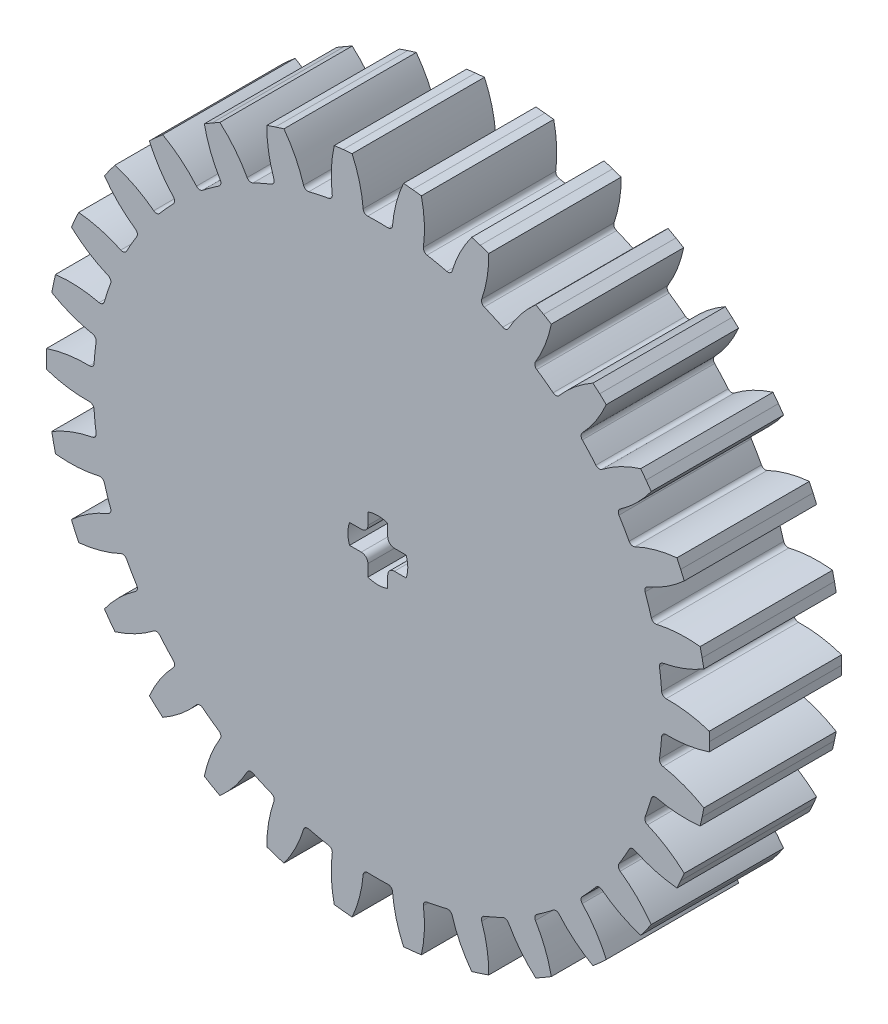
SolidWorks part; units mm, degrees
ref_plane "Front Plane" through (0, 0, 0) normal (0, 0, 1) x (1, 0, 0)
ref_plane "Top Plane" through (0, 0, 0) normal (0, 1, 0) x (1, 0, 0)
ref_plane "Right Plane" through (0, 0, 0) normal (1, 0, 0) x (0, 0, -1)
sketch "Sketch1" plane through (0, 0, 0) normal (0, 0, 1) x (1, 0, 0)
  line L0 (0, 0) -> (74.4139, 0) construction
  line L1 (0, 0) -> (21.3748, 2.2466) construction
  line L2 (0, 0) -> (74.4139, 4.0301) construction
  line L3 (0, 0) -> (74.4139, 2.0136) construction
  line L4 (25.0408, 0.6776) -> (25.05, 0)
  line L5 (0, 0) -> (21.3748, -2.2466) construction
  line L6 (0, 0) -> (21.3748, 2.2466)
  line L7 (0, 0) -> (21.3748, -2.2466) construction
  line L8 (0, 0) -> (21.3748, -2.2466)
  line L9 (25.0408, -0.6776) -> (25.05, 0)
  circle A0 centre (0, 0) radius 25.05 construction
  circle A1 centre (0, 0) radius 23.3875 construction
  circle A2 centre (0, 0) radius 21.4925 construction
  arc A3 (21.461, 1.1623) -> (25.0408, 0.6776) centre (21.9818, -8.4533) cw
  arc A4 (21.461, 1.1623) -> (21.3748, 2.2466) centre (0, 0) ccw
  arc A5 (21.461, -1.1623) -> (21.3748, -2.2466) centre (0, 0) cw
  arc A6 (21.461, -1.1623) -> (25.0408, -0.6776) centre (21.9818, 8.4533) ccw
  dimension "D1" = 50.1
  dimension "D2" = 1.6625
  dimension "D7" = 1.895
  dimension "D4" = 6
  dimension "D5" = 3.1
  dimension "D6" = 1.55
extrude "Boss-Extrude1" add sketch "Sketch1" along normal blind 10
fillet "Fillet1" radius 0.3325 2 edges at (21.461, 1.1623, 5) (21.461, -1.1623, 5)
pattern_circular "CirPattern1" count 30 over 360 about axis through (0, 0, 0) along (0, 0, 1) of "Boss-Extrude1", "Fillet1"
sketch "Sketch2" plane through (0, 0, 0) normal (0, 0, -1) x (-1, 0, 0)
  line L0 (0.75, 2.1372) -> (0.75, 1.25)
  line L1 (1.25, 0.75) -> (2.1372, 0.75)
  line L2 (2.265, 0) -> (-2.265, 0) construction
  line L3 (0, 2.265) -> (0, -2.265) construction
  line L4 (1.25, -0.75) -> (2.1372, -0.75)
  line L5 (0.75, -2.1372) -> (0.75, -1.25)
  line L6 (-0.75, -2.1372) -> (-0.75, -1.25)
  line L7 (-1.25, -0.75) -> (-2.1372, -0.75)
  line L8 (-1.25, 0.75) -> (-2.1372, 0.75)
  line L9 (-0.75, 2.1372) -> (-0.75, 1.25)
  arc A0 (-2.1372, -0.75) -> (-2.1372, 0.75) centre (0, 0) cw
  circle A1 centre (0, 0) radius 2.265 construction
  circle A2 centre (0, 0) radius 1.2374 construction
  arc A3 (-0.75, 2.1372) -> (0.75, 2.1372) centre (0, 0) cw
  arc A4 (-1.25, -0.75) -> (-0.75, -1.25) centre (-1.25, -1.25) cw
  arc A5 (0.75, -2.1372) -> (-0.75, -2.1372) centre (0, 0) cw
  arc A6 (2.1372, 0.75) -> (2.1372, -0.75) centre (0, 0) cw
  arc A7 (1.25, -0.75) -> (0.75, -1.25) centre (1.25, -1.25) ccw
  arc A8 (1.25, 0.75) -> (0.75, 1.25) centre (1.25, 1.25) cw
  arc A9 (-1.25, 0.75) -> (-0.75, 1.25) centre (-1.25, 1.25) ccw
  dimension "D1" = 4.53
  dimension "D2" = 0.5
  dimension "D5" = 2.4749
  dimension "D3" = 1.5
  dimension "D4" = 1.5
extrude "Cut-Extrude1" cut sketch "Sketch2" against normal up to next
